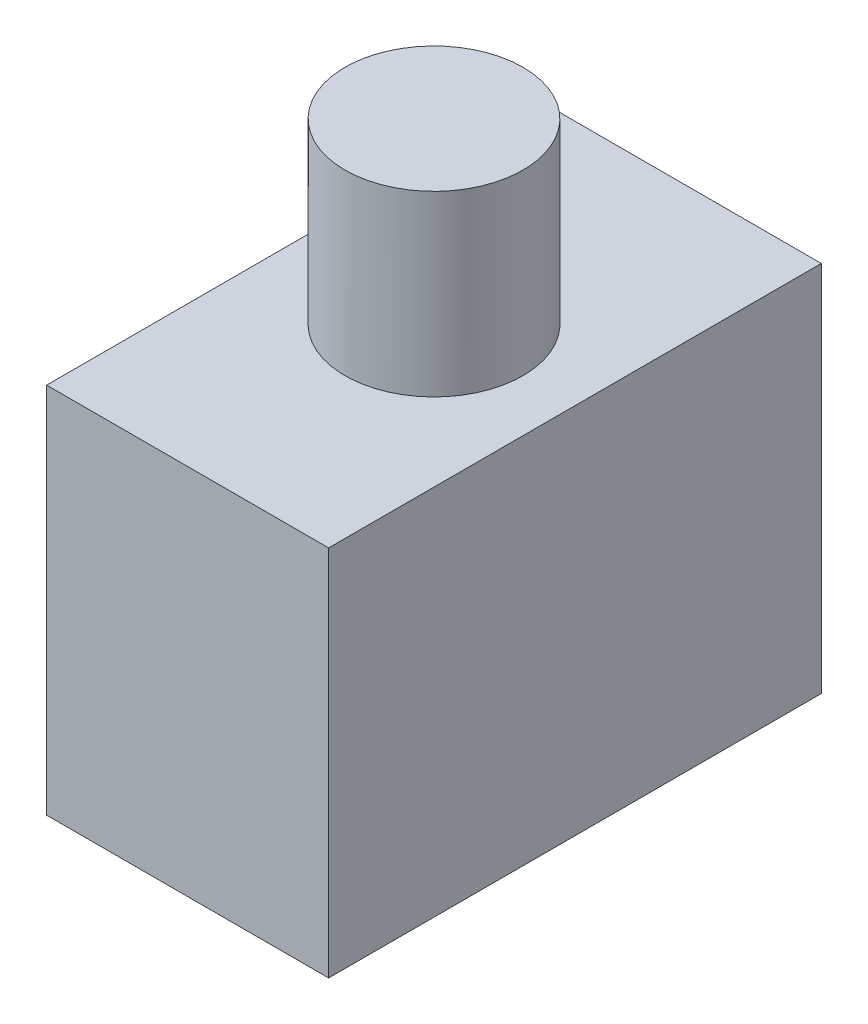
SolidWorks part; units mm, degrees
ref_plane "Front Plane" through (0, 0, 0) normal (0, 0, 1) x (1, 0, 0)
ref_plane "Top Plane" through (0, 0, 0) normal (0, 1, 0) x (1, 0, 0)
ref_plane "Right Plane" through (0, 0, 0) normal (1, 0, 0) x (0, 0, -1)
sketch "Sketch1" plane through (0, 0, 0) normal (0, 1, 0) x (1, 0, 0)
  line L1 (-9.5, -16.6) -> (9.5, -16.6)
  line L2 (-9.5, -16.6) -> (-9.5, 16.6)
  line L3 (-9.5, 16.6) -> (9.5, 16.6)
  line L4 (9.5, -16.6) -> (9.5, 16.6)
  line L5 (-9.5, -16.6) -> (9.5, 16.6) construction
  line L6 (-9.5, 16.6) -> (9.5, -16.6) construction
  point P0 (0, 0)
  dimension "D1" = 19
  dimension "D2" = 33.2
extrude "Boss-Extrude1" add sketch "Sketch1" along normal blind 25.1
sketch "Sketch2" plane through (0, 25.1, 0) normal (0, 1, 0) x (-1, 0, 0)
  circle A0 centre (0, 0) radius 6
  dimension "D1" = 12
extrude "Boss-Extrude2" add sketch "Sketch2" along normal blind 12
